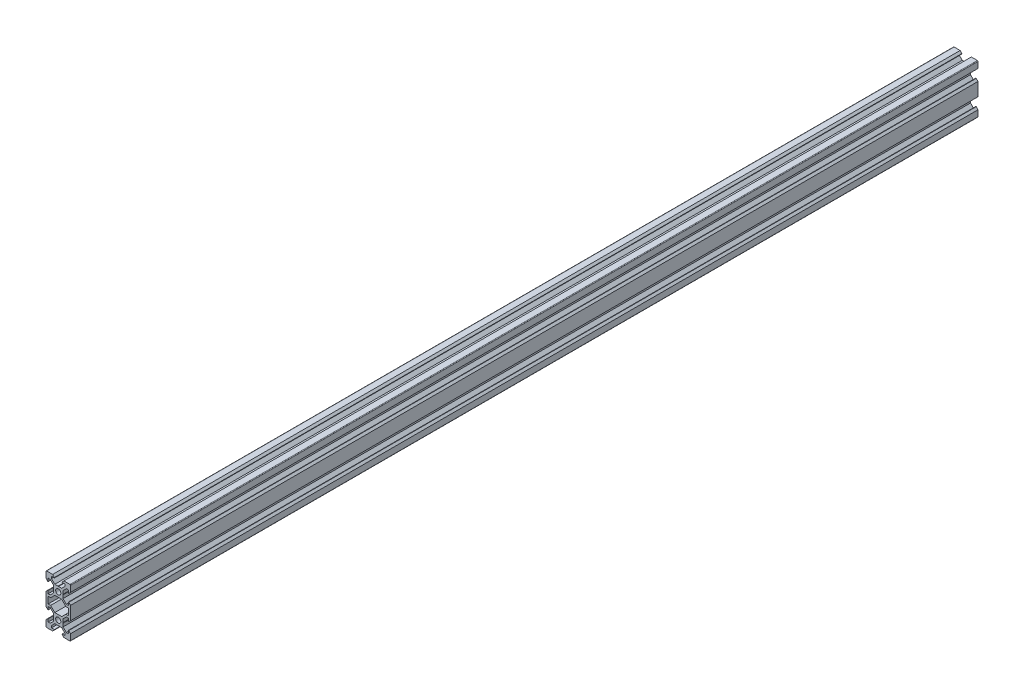
SolidWorks part; units mm, degrees
material "6061-T6 (SS)"
ref_plane "Front Plane" through (0, 0, 0) normal (0, 0, 1) x (1, 0, 0)
ref_plane "Top Plane" through (0, 0, 0) normal (0, 1, 0) x (1, 0, 0)
ref_plane "Right Plane" through (0, 0, 0) normal (1, 0, 0) x (0, 0, -1)
sketch "Sketch1" plane through (0, 0, 0) normal (0, 0, 1) x (1, 0, 0)
  line L0 (0, 0) -> (10, 0) construction
  line L1 (9.5, -20) -> (-9.5, -20)
  line L2 (10, -19.5) -> (10, 19.5)
  line L3 (9.5, 20) -> (-9.5, 20)
  line L4 (-10, -19.5) -> (-10, 19.5)
  line L5 (10, -20) -> (-10, 20) construction
  line L6 (10, 20) -> (-10, -20) construction
  circle A0 centre (0, 10) radius 2.1
  circle A1 centre (0, -10) radius 2.1
  arc A2 (-9.5, -20) -> (-10, -19.5) centre (-9.5, -19.5) cw
  arc A3 (9.5, -20) -> (10, -19.5) centre (9.5, -19.5) ccw
  arc A4 (10, 19.5) -> (9.5, 20) centre (9.5, 19.5) ccw
  arc A5 (-9.5, 20) -> (-10, 19.5) centre (-9.5, 19.5) ccw
  point P0 (0, 0)
  line B0 (0, 10) -> (0, 20) construction
  line B1 (0, 13.69) -> (-0.21, 13.9)
  line B2 (-0.21, 13.9) -> (-2.8393, 13.9)
  line B3 (-2.8393, 13.9) -> (-5.5, 16.5607)
  line B4 (-5.5, 16.5607) -> (-5.5, 18.2)
  line B5 (-5.5, 18.2) -> (-3.125, 18.2)
  line B6 (-3.125, 18.2) -> (-3.125, 18.545)
  line B7 (-3.125, 18.545) -> (-4.58, 20)
  line B8 (-4.58, 20) -> (4.58, 20)
  line B9 (0, 10) -> (-5.9132, 15.9132) construction
  line B10 (3.125, 18.545) -> (4.58, 20)
  line B11 (3.125, 18.2) -> (3.125, 18.545)
  line B12 (5.5, 18.2) -> (3.125, 18.2)
  line B13 (5.5, 16.5607) -> (5.5, 18.2)
  line B14 (2.8393, 13.9) -> (5.5, 16.5607)
  line B15 (0.21, 13.9) -> (2.8393, 13.9)
  line B16 (0, 13.69) -> (0.21, 13.9)
  line B17 (0, 10) -> (-10, 10) construction
  line B18 (-3.69, 10) -> (-3.9, 9.79)
  line B19 (-3.9, 9.79) -> (-3.9, 7.1607)
  line B20 (-3.9, 7.1607) -> (-6.5607, 4.5)
  line B21 (-6.5607, 4.5) -> (-8.2, 4.5)
  line B22 (-8.2, 4.5) -> (-8.2, 6.875)
  line B23 (-8.2, 6.875) -> (-8.545, 6.875)
  line B24 (-8.545, 6.875) -> (-10, 5.42)
  line B25 (-10, 5.42) -> (-10, 14.58)
  line B26 (0, 10) -> (-5.9132, 4.0868) construction
  line B27 (-8.545, 13.125) -> (-10, 14.58)
  line B28 (-8.2, 13.125) -> (-8.545, 13.125)
  line B29 (-8.2, 15.5) -> (-8.2, 13.125)
  line B30 (-6.5607, 15.5) -> (-8.2, 15.5)
  line B31 (-3.9, 12.8393) -> (-6.5607, 15.5)
  line B32 (-3.9, 10.21) -> (-3.9, 12.8393)
  line B33 (-3.69, 10) -> (-3.9, 10.21)
  line B34 (0, -10) -> (-10, -10) construction
  line B35 (-3.69, -10) -> (-3.9, -10.21)
  line B36 (-3.9, -10.21) -> (-3.9, -12.8393)
  line B37 (-3.9, -12.8393) -> (-6.5607, -15.5)
  line B38 (-6.5607, -15.5) -> (-8.2, -15.5)
  line B39 (-8.2, -15.5) -> (-8.2, -13.125)
  line B40 (-8.2, -13.125) -> (-8.545, -13.125)
  line B41 (-8.545, -13.125) -> (-10, -14.58)
  line B42 (-10, -14.58) -> (-10, -5.42)
  line B43 (0, -10) -> (-5.9132, -15.9132) construction
  line B44 (-8.545, -6.875) -> (-10, -5.42)
  line B45 (-8.2, -6.875) -> (-8.545, -6.875)
  line B46 (-8.2, -4.5) -> (-8.2, -6.875)
  line B47 (-6.5607, -4.5) -> (-8.2, -4.5)
  line B48 (-3.9, -7.1607) -> (-6.5607, -4.5)
  line B49 (-3.9, -9.79) -> (-3.9, -7.1607)
  line B50 (-3.69, -10) -> (-3.9, -9.79)
  line B51 (0, -10) -> (0, -20) construction
  line B52 (0, -13.69) -> (0.21, -13.9)
  line B53 (0.21, -13.9) -> (2.8393, -13.9)
  line B54 (2.8393, -13.9) -> (5.5, -16.5607)
  line B55 (5.5, -16.5607) -> (5.5, -18.2)
  line B56 (5.5, -18.2) -> (3.125, -18.2)
  line B57 (3.125, -18.2) -> (3.125, -18.545)
  line B58 (3.125, -18.545) -> (4.58, -20)
  line B59 (4.58, -20) -> (-4.58, -20)
  line B60 (0, -10) -> (5.9132, -15.9132) construction
  line B61 (-3.125, -18.545) -> (-4.58, -20)
  line B62 (-3.125, -18.2) -> (-3.125, -18.545)
  line B63 (-5.5, -18.2) -> (-3.125, -18.2)
  line B64 (-5.5, -16.5607) -> (-5.5, -18.2)
  line B65 (-2.8393, -13.9) -> (-5.5, -16.5607)
  line B66 (-0.21, -13.9) -> (-2.8393, -13.9)
  line B67 (0, -13.69) -> (-0.21, -13.9)
  line B68 (0, -10) -> (10, -10) construction
  line B69 (3.69, -10) -> (3.9, -9.79)
  line B70 (3.9, -9.79) -> (3.9, -7.1607)
  line B71 (3.9, -7.1607) -> (6.5607, -4.5)
  line B72 (6.5607, -4.5) -> (8.2, -4.5)
  line B73 (8.2, -4.5) -> (8.2, -6.875)
  line B74 (8.2, -6.875) -> (8.545, -6.875)
  line B75 (8.545, -6.875) -> (10, -5.42)
  line B76 (10, -5.42) -> (10, -14.58)
  line B77 (0, -10) -> (5.9132, -4.0868) construction
  line B78 (8.545, -13.125) -> (10, -14.58)
  line B79 (8.2, -13.125) -> (8.545, -13.125)
  line B80 (8.2, -15.5) -> (8.2, -13.125)
  line B81 (6.5607, -15.5) -> (8.2, -15.5)
  line B82 (3.9, -12.8393) -> (6.5607, -15.5)
  line B83 (3.9, -10.21) -> (3.9, -12.8393)
  line B84 (3.69, -10) -> (3.9, -10.21)
  line B85 (0, 10) -> (10, 10) construction
  line B86 (3.69, 10) -> (3.9, 10.21)
  line B87 (3.9, 10.21) -> (3.9, 12.8393)
  line B88 (3.9, 12.8393) -> (6.5607, 15.5)
  line B89 (6.5607, 15.5) -> (8.2, 15.5)
  line B90 (8.2, 15.5) -> (8.2, 13.125)
  line B91 (8.2, 13.125) -> (8.545, 13.125)
  line B92 (8.545, 13.125) -> (10, 14.58)
  line B93 (10, 14.58) -> (10, 5.42)
  line B94 (0, 10) -> (5.9132, 15.9132) construction
  line B95 (8.545, 6.875) -> (10, 5.42)
  line B96 (8.2, 6.875) -> (8.545, 6.875)
  line B97 (8.2, 4.5) -> (8.2, 6.875)
  line B98 (6.5607, 4.5) -> (8.2, 4.5)
  line B99 (3.9, 7.1607) -> (6.5607, 4.5)
  line B100 (3.9, 9.79) -> (3.9, 7.1607)
  line B101 (3.69, 10) -> (3.9, 9.79)
  line B102 (-8.2, -2.7) -> (-8.2, 2.7)
  line B103 (-8.2, 2.7) -> (-6.2393, 2.7)
  line B104 (-6.2393, 2.7) -> (-2.8393, 6.1)
  line B105 (-2.8393, 6.1) -> (2.8393, 6.1)
  line B106 (0, 6.1) -> (0, 0) construction
  line B107 (0, 0) -> (-8.2, 0) construction
  line B108 (6.2393, 2.7) -> (2.8393, 6.1)
  line B109 (8.2, 2.7) -> (6.2393, 2.7)
  line B110 (8.2, -2.7) -> (8.2, 2.7)
  line B111 (8.2, -2.7) -> (6.2393, -2.7)
  line B112 (6.2393, -2.7) -> (2.8393, -6.1)
  line B113 (-2.8393, -6.1) -> (2.8393, -6.1)
  line B114 (-6.2393, -2.7) -> (-2.8393, -6.1)
  line B115 (-8.2, -2.7) -> (-6.2393, -2.7)
  line B116 (0, 6.1) -> (0, 10) construction
  line B117 (0, 10) -> (-5.0927, 4.9073) construction
  dimension "D4" = 4.2
  dimension "D5" = 0.5
  dimension "D1" = 20
  dimension "D2" = 40
  dimension "D3" = 20
sketch_block_instance "V Slot 1-4"
sketch_block "V Slot 1" parameters "D1"=10, "D2"=11, "D3"=4.3, "D4"=1.8, "D5"=0.21, "D6"=45, "D7"=9.16, "D8"=1.5, "D9"=6.25
sketch_block_instance "V Slot 1-5"
sketch_block_instance "V Slot 1-6"
sketch_block_instance "V Slot 1-7"
sketch_block_instance "V Slot 1-8"
sketch_block_instance "V Slot 1-9"
sketch_block_instance "Center Cutout 1-1"
sketch_block "Center Cutout 1" parameters "D1"=5.4, "D2"=12.2, "D3"=8.2, "D4"=45, "D5"=10, "D6"=1.5
extrude "Boss-Extrude1" add sketch "Sketch1" along normal blind 740 contours B101 B86 B87 B88 B89 B90 B91 B92 L2 A4 L3 B10 B11 B12 B13 B14 B15 B16 B1 B2 B3 B4 B5 B6 B7 A5 L4 B27 B28 B29 B30 B31 B32 B33 B18 B19 B20 B21 B22 B23 B24 B44 B45 B46 B47 B48 B49 B50 B35
